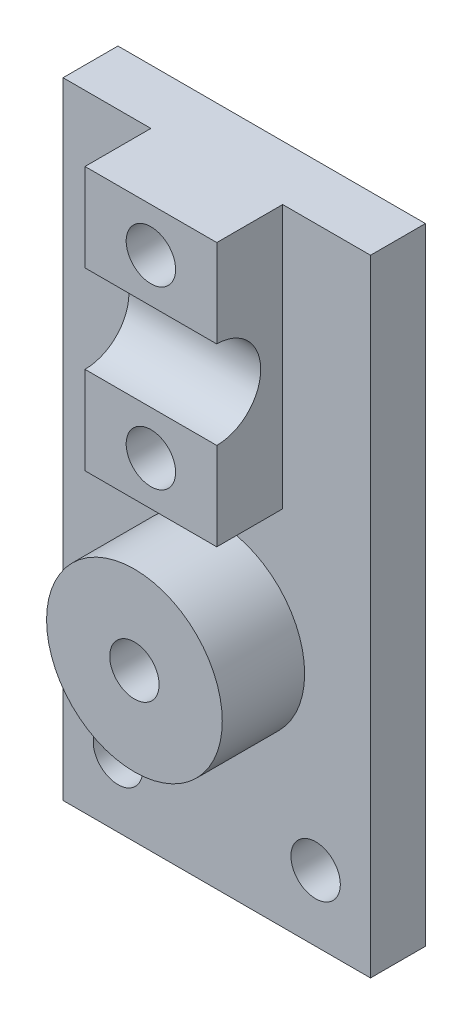
SolidWorks part; units mm, degrees
material "Printed PLA"
ref_plane "Front Plane" through (0, 0, 0) normal (0, 0, 1) x (1, 0, 0)
ref_plane "Top Plane" through (0, 0, 0) normal (0, 1, 0) x (1, 0, 0)
ref_plane "Right Plane" through (0, 0, 0) normal (1, 0, 0) x (0, 0, -1)
sketch "Sketch1" plane through (0, 0, 0) normal (0, 0, 1) x (1, 0, 0)
  line L1 (-14, 0) -> (14, 0)
  line L2 (-14, 0) -> (-14, -57)
  line L3 (-14, -57) -> (14, -57)
  line L4 (14, 0) -> (14, -57)
  dimension "D1" = 28
  dimension "D2" = 57
extrude "Boss-Extrude1" add sketch "Sketch1" along normal blind 5
sketch "Sketch2" plane through (0, 0, 0) normal (1, 0, 0) x (0, 0, -1)
  line L0 (-5, 0) -> (-5, -24)
  line L1 (-5, -57) -> (-5, 0) construction
  line L2 (-5, -24) -> (-11, -24)
  line L3 (-11, -24) -> (-11, -16)
  line L4 (-11, -8) -> (-11, 0)
  line L5 (-11, 0) -> (-5, 0)
  arc A0 (-11, -16) -> (-11, -8) centre (-11, -12) ccw
  dimension "D1" = 4
  dimension "D2" = 6
  dimension "D3" = 8
extrude "Boss-Extrude2" add sketch "Sketch2" against normal mid plane 12
sketch "Sketch3" plane through (0, 0, 11) normal (0, 0, 1) x (1, 0, 0)
  line L0 (0, -20) -> (0, -4) construction
  line L1 (0, -12) -> (6, -12) construction
  line L2 (6, -16) -> (6, -8) construction
  line L3 (0, -4) -> (0, 0) construction
  line L4 (-6, 0) -> (6, 0) construction
  circle A0 centre (0, -4) radius 2.25
  circle A1 centre (0, -20) radius 2.25
  dimension "D1" = 4.5
  dimension "D2" = 16
extrude "Cut-Extrude1" cut sketch "Sketch3" against normal through all
sketch "Sketch4" plane through (0, 0, 5) normal (0, 0, 1) x (1, 0, 0)
  line L0 (9, -51) -> (-9, -51) construction
  line L1 (0, -51) -> (0, -57) construction
  line L2 (-14, -57) -> (14, -57) construction
  circle A0 centre (-9, -51) radius 2.25
  circle A1 centre (9, -51) radius 2.25
  dimension "D1" = 4.5
  dimension "D2" = 6
  dimension "D3" = 18
extrude "Cut-Extrude2" cut sketch "Sketch4" against normal through all
sketch "Sketch5" plane through (0, 0, 5) normal (0, 0, 1) x (1, 0, 0)
  line L0 (0, -36) -> (0, 0) construction
  circle A0 centre (0, -36) radius 8
  dimension "D1" = 16
  dimension "D2" = 36
extrude "Boss-Extrude3" add sketch "Sketch5" along normal blind 7.5
sketch "Sketch6" plane through (0, 0, 12.5) normal (0, 0, 1) x (1, 0, 0)
  circle A0 centre (0, -36) radius 2.25
  dimension "D1" = 4.5
extrude "Cut-Extrude3" cut sketch "Sketch6" against normal through all
